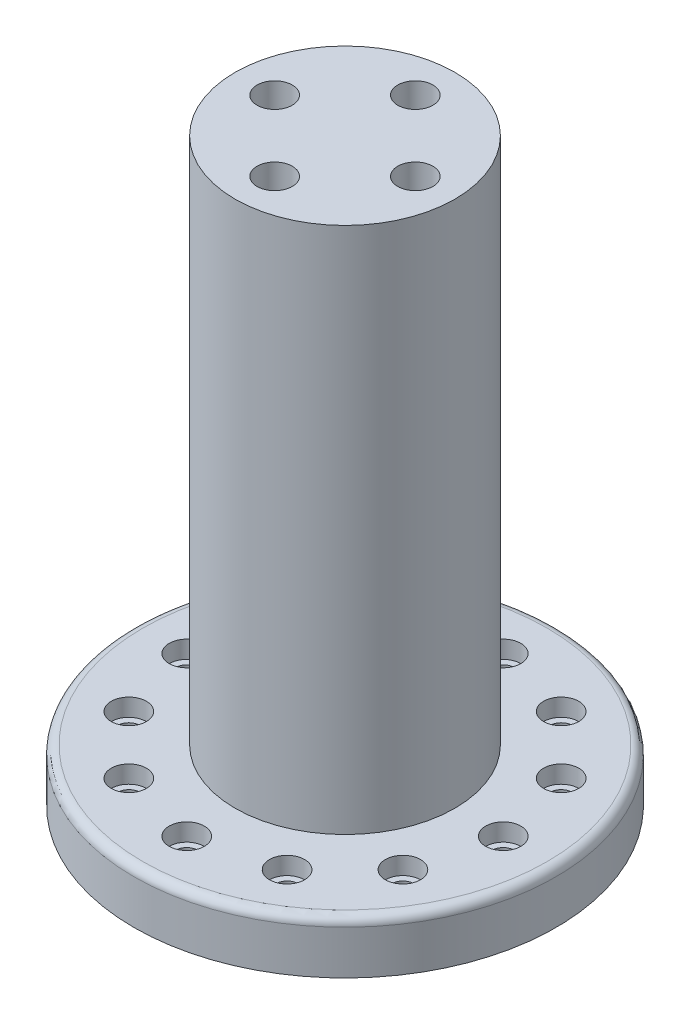
SolidWorks part; units mm, degrees
ref_plane "Front Plane" through (0, 0, 0) normal (0, 0, 1) x (1, 0, 0)
ref_plane "Top Plane" through (0, 0, 0) normal (0, 1, 0) x (1, 0, 0)
ref_plane "Right Plane" through (0, 0, 0) normal (1, 0, 0) x (0, 0, -1)
sketch "Sketch1" plane through (0, 0, 0) normal (0, 1, 0) x (1, 0, 0)
  line L0 (0, 0) -> (-22595.0444, 0) construction
  line L1 (0, 0) -> (0, -22595.0444) construction
  circle A0 centre (0, 0) radius 24
  dimension "D1" = 48
extrude "Boss-Extrude1" add sketch "Sketch1" along normal blind 6
sketch "Sketch2" plane through (0, 6, 0) normal (0, 1, 0) x (1, 0, 0)
  line L0 (0, 0) -> (-50000, 0) construction
  line L1 (0, 0) -> (0, -50000) construction
  circle A0 centre (0, 0) radius 18 construction
  circle A1 centre (0, 18) radius 2
  circle A2 centre (9, 15.5885) radius 2
  circle A3 centre (15.5885, 9) radius 2
  circle A4 centre (18, 0) radius 2
  circle A5 centre (15.5885, -9) radius 2
  circle A6 centre (9, -15.5885) radius 2
  circle A7 centre (0, -18) radius 2
  circle A8 centre (-9, -15.5885) radius 2
  circle A9 centre (-15.5885, -9) radius 2
  circle A10 centre (-18, 0) radius 2
  circle A11 centre (-15.5885, 9) radius 2
  circle A12 centre (-9, 15.5885) radius 2
  point P34 (0, 0)
  dimension "D1" = 36
  dimension "D2" = 4
  dimension "D3" = 12
extrude "Cut-Extrude1" cut sketch "Sketch2" against normal blind 2
sketch "Sketch3" plane through (0, 4, 0) normal (0, 1, 0) x (1, 0, 0)
  line L0 (0, 0) -> (-50000, 0) construction
  line L1 (0, 0) -> (0, -50000) construction
  circle A0 centre (0, 0) radius 18 construction
  circle A1 centre (0, 18) radius 1.25
  circle A2 centre (9, 15.5885) radius 1.25
  circle A3 centre (15.5885, 9) radius 1.25
  circle A4 centre (18, 0) radius 1.25
  circle A5 centre (15.5885, -9) radius 1.25
  circle A6 centre (9, -15.5885) radius 1.25
  circle A7 centre (0, -18) radius 1.25
  circle A8 centre (-9, -15.5885) radius 1.25
  circle A9 centre (-15.5885, -9) radius 1.25
  circle A10 centre (-18, 0) radius 1.25
  circle A11 centre (-15.5885, 9) radius 1.25
  circle A12 centre (-9, 15.5885) radius 1.25
  point P34 (0, 0)
  dimension "D1" = 36
  dimension "D2" = 2.5
  dimension "D3" = 12
extrude "Cut-Extrude2" cut sketch "Sketch3" against normal through all
sketch "Sketch4" plane through (0, 6, 0) normal (0, 1, 0) x (1, 0, 0)
  line L0 (0, 0) -> (-50000, 0) construction
  line L1 (0, 0) -> (0, -50000) construction
  circle A0 centre (0, 0) radius 12.5
  dimension "D1" = 25
extrude "Boss-Extrude2" add sketch "Sketch4" along normal blind 60
sketch "Sketch5" plane through (0, 0, 0) normal (0, -1, 0) x (1, 0, 0)
  line L0 (0, 0) -> (-50000, 0) construction
  line L1 (0, 0) -> (0, -50000) construction
  circle A0 centre (0, 0) radius 8.5
  dimension "D1" = 17
extrude "Cut-Extrude3" cut sketch "Sketch5" against normal blind 5
fillet "Fillet1" radius 1 1 edges at (0, 6, 24)
sketch "Sketch6" plane through (0, 66, 0) normal (0, 1, 0) x (1, 0, 0)
  line L0 (0, 0) -> (-50000, 0) construction
  line L1 (0, 0) -> (0, -50000) construction
  circle A0 centre (0, 0) radius 8 construction
  circle A2 centre (0, 8) radius 2
  circle A3 centre (8, 0) radius 2
  circle A4 centre (0, -8) radius 2
  circle A5 centre (-8, 0) radius 2
  point P19 (0, 0)
  dimension "D1" = 16
  dimension "D2" = 4
  dimension "D3" = 4
extrude "Cut-Extrude4" cut sketch "Sketch6" against normal blind 20
